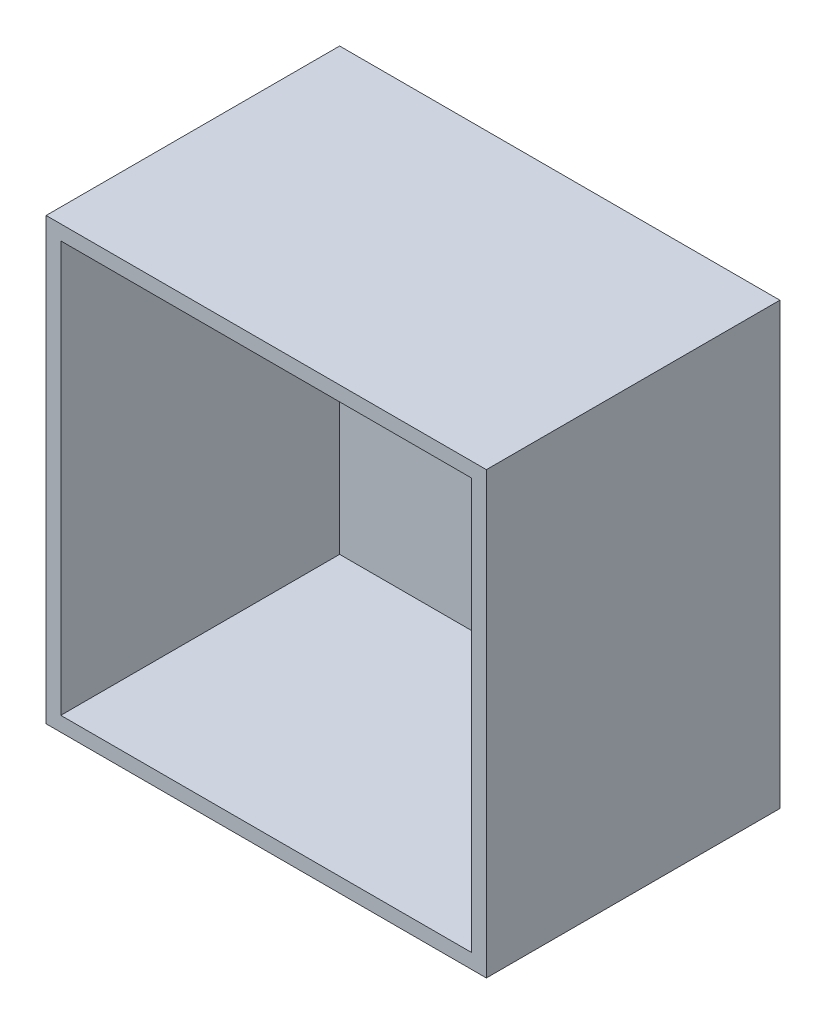
SolidWorks part; units mm, degrees
ref_plane "Front Plane" through (0, 0, 0) normal (0, 0, 1) x (1, 0, 0)
ref_plane "Top Plane" through (0, 0, 0) normal (0, 1, 0) x (1, 0, 0)
ref_plane "Right Plane" through (0, 0, 0) normal (1, 0, 0) x (0, 0, -1)
sketch "Sketch2" plane through (0, 0, 0) normal (0, 0, 1) x (1, 0, 0)
  line L1 (0, 0) -> (76.2, 0)
  line L2 (0, 0) -> (0, 76.2)
  line L3 (0, 76.2) -> (76.2, 76.2)
  line L4 (76.2, 0) -> (76.2, 76.2)
  dimension "D1" = 76.2
  dimension "D2" = 76.2
extrude "Boss-Extrude1" add sketch "Sketch2" along normal blind 50.8
shell "Shell1" thickness 2.54
